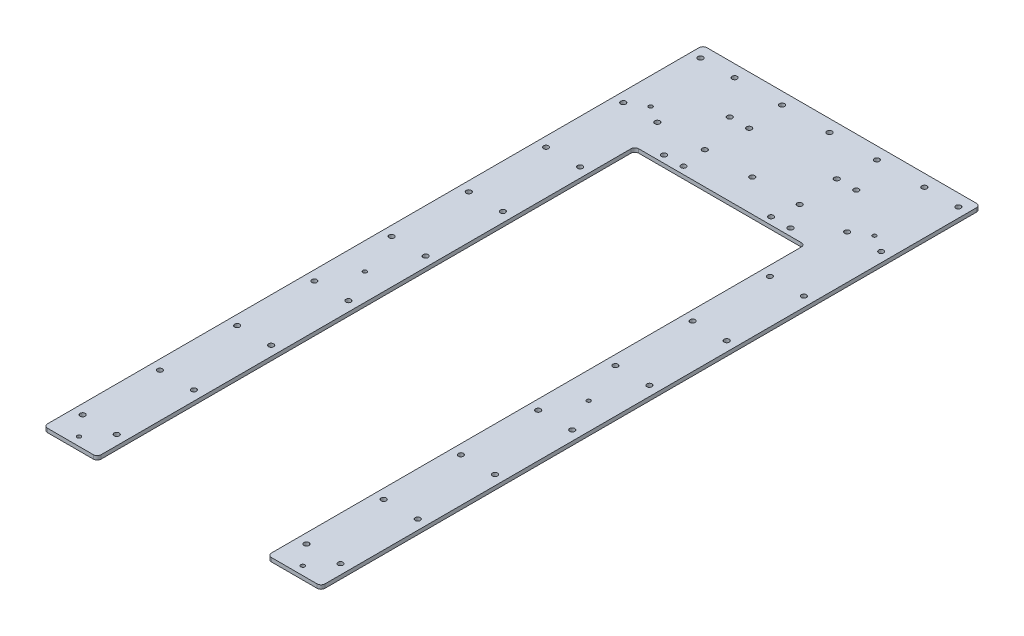
SolidWorks part; units mm, degrees
ref_plane "Front Plane" through (0, 0, 0) normal (0, 0, 1) x (1, 0, 0)
ref_plane "Top Plane" through (0, 0, 0) normal (0, 1, 0) x (1, 0, 0)
ref_plane "Right Plane" through (0, 0, 0) normal (1, 0, 0) x (0, 0, -1)
sketch "Sketch1" plane through (0, 0, 0) normal (0, 1, 0) x (1, 0, 0)
  line L0 (92, 271) -> (92, -271) construction
  line L1 (-114, -271) -> (-70, -271)
  line L2 (-114, -271) -> (-114, 271)
  line L3 (-114, 271) -> (114, 271)
  line L4 (114, -271) -> (114, 271)
  line L5 (-114, -271) -> (114, 271) construction
  line L6 (-114, 271) -> (114, -271) construction
  line L7 (106, 261) -> (106, 197.5) construction
  line L8 (0, 271) -> (0, -271) construction
  line L9 (-114, -29) -> (114, -29) construction
  line L10 (78, 261) -> (49, 261) construction
  line L11 (70, -271) -> (114, -271)
  line L13 (-70, -271) -> (-70, 171)
  line L14 (-70, 171) -> (70, 171)
  line L15 (70, -271) -> (70, 171)
  line L16 (-58.0332, 204) -> (-23.7286, 204) construction
  line L17 (-92, 271) -> (-92, -271) construction
  circle A0 centre (106, 261) radius 2.1
  circle A1 centre (106, 197.5) radius 2.1
  circle A2 centre (106, 134) radius 2.1
  circle A3 centre (106, 70.5) radius 2.1
  circle A4 centre (106, 7) radius 2.1
  circle A5 centre (106, -56.5) radius 2.1
  circle A6 centre (106, -120) radius 2.1
  circle A7 centre (106, -183.5) radius 2.1
  circle A11 centre (78, -247) radius 2.1
  circle A12 centre (78, -183.5) radius 2.1
  circle A13 centre (78, -120) radius 2.1
  circle A14 centre (78, -56.5) radius 2.1
  circle A15 centre (78, 7) radius 2.1
  circle A16 centre (78, 70.5) radius 2.1
  circle A17 centre (78, 134) radius 2.1
  circle A18 centre (78, 197.5) radius 2.1
  circle A19 centre (78, 261) radius 2.1
  circle A20 centre (92, -29) radius 1.6
  circle A21 centre (92, 206) radius 1.6
  circle A22 centre (92, -264) radius 1.6
  circle A23 centre (-106, 261) radius 2.1
  circle A24 centre (-78, 261) radius 2.1
  circle A25 centre (-92, 206) radius 1.6
  circle A26 centre (-78, 70.5) radius 2.1
  circle A27 centre (-106, 70.5) radius 2.1
  circle A28 centre (-106, 134) radius 2.1
  circle A29 centre (-106, 197.5) radius 2.1
  circle A30 centre (-92, -264) radius 1.6
  circle A31 centre (-92, -29) radius 1.6
  circle A32 centre (-78, 7) radius 2.1
  circle A33 centre (-78, -56.5) radius 2.1
  circle A34 centre (-78, -120) radius 2.1
  circle A35 centre (-78, -183.5) radius 2.1
  circle A36 centre (-78, -247) radius 2.1
  circle A39 centre (-106, -247) radius 2.1
  circle A40 centre (-106, -183.5) radius 2.1
  circle A41 centre (-106, -120) radius 2.1
  circle A42 centre (-106, -56.5) radius 2.1
  circle A43 centre (-106, 7) radius 2.1
  circle A44 centre (-78, 197.5) radius 2.1
  circle A45 centre (-78, 134) radius 2.1
  circle A57 centre (-52, 177) radius 2.1
  circle A58 centre (-36, 177) radius 2.1
  circle A59 centre (-36, 231) radius 2.1
  circle A60 centre (-52, 231) radius 2.1
  circle A61 centre (36, 177) radius 2.1
  circle A62 centre (52, 177) radius 2.1
  circle A63 centre (52, 231) radius 2.1
  circle A64 centre (36, 231) radius 2.1
  circle A65 centre (-39, 197.5) radius 2.1
  circle A66 centre (-39, 261) radius 2.1
  circle A67 centre (106, -247) radius 2.1
  circle A68 centre (0, 197.5) radius 2.1
  circle A69 centre (0, 261) radius 2.1
  circle A70 centre (39, 197.5) radius 2.1
  circle A71 centre (39, 261) radius 2.1
  point P0 (0, 0)
  dimension "D4" = 4.2
  dimension "D10" = 3.2
  dimension "D11" = 3.2
  dimension "D21" = 4.2
  dimension "D22" = 4.2
  dimension "D1" = 228
  dimension "D2" = 542
  dimension "D3" = 22
  dimension "D5" = 10
  dimension "D6" = 14
  dimension "D8" = 63.5
  dimension "D9" = 300
  dimension "D12" = 235
  dimension "D15" = 29
  dimension "D18" = 100
  dimension "D19" = 6
  dimension "D20" = 18
  dimension "D23" = 16
  dimension "D24" = 27
  dimension "D16" = 8
  dimension "D17" = 70
  dimension "D25" = 70
  dimension "D7" = 9
  dimension "D13" = 4
extrude "Boss-Extrude1" add sketch "Sketch1" along normal blind 3.175
fillet "Fillet1" radius 3.2 8 edges at (-114, 1.5875, -271) (114, 1.5875, -271) (70, 1.5875, -171) (-70, 1.5875, -171) (114, 1.5875, 271) (70, 1.5875, 271) (-114, 1.5875, 271) (-70, 1.5875, 271)
equation "\"m3\"= 3.2"
equation "\"m4\"= 4.2"
equation "\"width\"=228"
equation "\"height\"= 600 - ( 58 / 2 ) - 29"
equation "\"D1@Sketch1\"=\"width\""
equation "\"D2@Sketch1\"=\"height\""
equation "\"D4@Sketch1\"=\"m4\""
equation "\"D10@Sketch1\"=\"m3\""
equation "\"D11@Sketch1\"=\"m3\""
equation "\"D21@Sketch1\"=\"m4\""
equation "\"D22@Sketch1\"=\"m4\""
